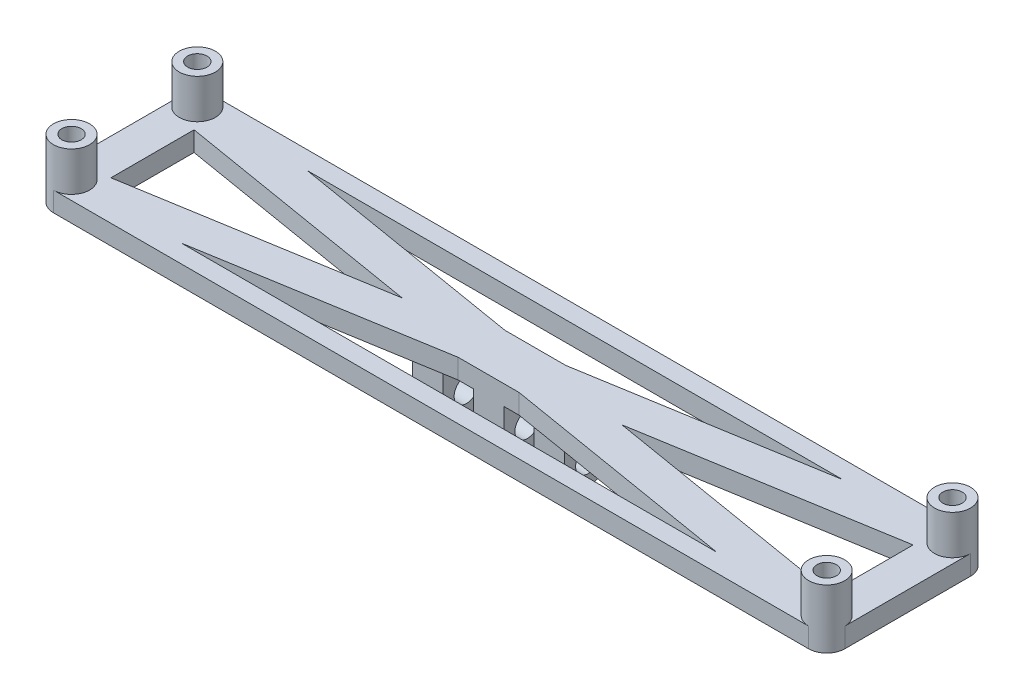
SolidWorks part; units mm, degrees
ref_plane "Front Plane" through (0, 0, 0) normal (0, 0, 1) x (1, 0, 0)
ref_plane "Top Plane" through (0, 0, 0) normal (0, 1, 0) x (1, 0, 0)
ref_plane "Right Plane" through (0, 0, 0) normal (1, 0, 0) x (0, 0, -1)
sketch "Sketch1" plane through (0, 0, 0) normal (0, 1, 0) x (1, 0, 0)
  line L1 (-38.36, 6.39) -> (-27.1925, 6.39) construction
  line L2 (-38.36, 6.39) -> (-38.36, -6.39) construction
  line L3 (-38.36, -6.39) -> (-36.525, -6.39) construction
  line L4 (38.36, 4.555) -> (38.36, 4.5297) construction
  line L7 (-38.0585, 8.2001) -> (-3.0899, 2.375) construction
  line L8 (-38.6615, 4.5799) -> (-11.1675, 0) construction
  line L10 (-38.6615, -4.5799) -> (-11.1675, 0) construction
  line L12 (11.1675, 0) -> (36.525, -4.224) construction
  line L13 (-3.0899, 2.375) -> (3.0899, 2.375) construction
  line L15 (-3.0899, -2.375) -> (3.0899, -2.375) construction
  line L17 (-38.36, 6.39) -> (-38.36, -6.39) construction
  line L18 (3.0899, 2.375) -> (16.1767, 4.555) construction
  line L19 (11.1675, 0) -> (36.525, 4.224) construction
  line L24 (3.0899, -2.375) -> (16.1767, -4.555) construction
  line L25 (-36.525, 6.39) -> (-36.525, -4.555) construction
  line L26 (-40.195, 6.39) -> (-40.195, -6.39) construction
  line L30 (-38.36, -6.39) -> (-36.525, -6.39) construction
  line L31 (-38.36, -4.555) -> (-36.525, -4.555) construction
  line L32 (-38.36, -8.225) -> (38.36, -8.225) construction
  line L33 (38.36, 4.555) -> (38.36, 4.5297) construction
  line L34 (40.195, 6.39) -> (40.195, -6.39) construction
  line L35 (36.525, 4.224) -> (36.525, -4.555) construction
  line L37 (16.1767, 4.555) -> (-38.36, 4.555) construction
  line L38 (38.36, 8.225) -> (-38.36, 8.225) construction
  line L39 (38.36, -4.5297) -> (38.6615, -4.5799) construction
  line L41 (-27.1925, 6.39) -> (-38.36, 6.39) construction
  line L42 (38.36, -4.5297) -> (38.36, -6.39) construction
  line L43 (38.36, -4.5297) -> (38.36, -6.39) construction
  line L44 (-16.1767, -4.555) -> (-3.0899, -2.375) construction
  line L45 (-16.1767, -4.555) -> (16.1767, -4.555) construction
  arc A0 (-38.0585, 8.2001) -> (-38.6615, 4.5799) centre (-38.36, 6.39) ccw construction
  arc A1 (38.0585, -8.2001) -> (38.6615, -4.5799) centre (38.36, -6.39) ccw construction
  arc A2 (-38.6615, -4.5799) -> (-38.0585, -8.2001) centre (-38.36, -6.39) ccw construction
  arc A3 (40.195, 6.39) -> (38.0585, 8.2001) centre (38.36, 6.39) ccw construction
  arc A4 (-36.525, 6.39) -> (-40.195, 6.39) centre (-38.36, 6.39) ccw construction
  arc A5 (-40.195, -6.39) -> (-36.525, -6.39) centre (-38.36, -6.39) ccw construction
  arc A8 (-38.36, -4.555) -> (-38.36, -8.225) centre (-38.36, -6.39) ccw construction
  arc A9 (38.36, -8.225) -> (38.36, -4.555) centre (38.36, -6.39) ccw construction
  arc A10 (40.195, 6.39) -> (38.0585, 8.2001) centre (38.36, 6.39) ccw construction
  arc A11 (38.0585, -8.2001) -> (40.195, -6.39) centre (38.36, -6.39) ccw construction
  arc A13 (-38.36, 8.225) -> (-38.36, 4.555) centre (-38.36, 6.39) ccw construction
  arc A14 (40.195, 6.39) -> (38.36, 8.225) centre (38.36, 6.39) ccw construction
  point P0 (0, 0)
  point P6 (0, 0)
  point P11 (0, 0)
  point P16 (0, 0)
  point P17 (-38.36, 0)
  point P26 (0, 6.39)
  point P35 (0, -6.39)
  point P43 (38.36, 0)
  dimension "D1" = 76.72
  dimension "D2" = 12.78
sketch "Sketch2" plane through (0, 0, 0) normal (0, 1, 0) x (1, 0, 0)
  line L0 (-38.36, 6.39) -> (38.36, -6.39) construction
  line L1 (38.36, -6.39) -> (-38.36, -6.39) construction
  line L2 (38.36, -6.39) -> (38.36, 6.39) construction
  line L3 (38.36, 6.39) -> (-38.36, 6.39) construction
  line L4 (-38.36, -6.39) -> (-38.36, 6.39) construction
  line L5 (38.36, -6.39) -> (-38.36, 6.39) construction
  line L6 (38.36, 6.39) -> (-38.36, -6.39) construction
  line L7 (-38.0585, 8.2001) -> (38.6615, -4.5799) construction
  line L8 (-38.6615, 4.5799) -> (38.0585, -8.2001) construction
  line L9 (-38.36, -6.39) -> (38.36, 6.39) construction
  line L10 (-38.6615, -4.5799) -> (38.0585, 8.2001) construction
  line L11 (-38.0585, -8.2001) -> (38.6615, 4.5799) construction
  line L12 (-38.36, 6.39) -> (-38.36, -6.39) construction
  line L19 (-36.525, 6.39) -> (-36.525, -6.39) construction
  line L20 (-40.195, 6.39) -> (-40.195, -6.39) construction
  line L21 (38.36, 6.39) -> (38.36, -6.39) construction
  line L22 (40.195, 6.39) -> (40.195, -6.39) construction
  line L23 (36.525, 6.39) -> (36.525, -6.39) construction
  line L24 (-38.36, 6.39) -> (38.36, 6.39) construction
  line L25 (-38.36, 8.225) -> (38.36, 8.225) construction
  line L26 (-38.36, 4.555) -> (38.36, 4.555) construction
  line L27 (-38.36, -6.39) -> (38.36, -6.39) construction
  line L28 (-38.36, -4.555) -> (38.36, -4.555) construction
  line L29 (-38.36, -8.225) -> (38.36, -8.225) construction
  line L31 (-7.715, 2.375) -> (7.715, 2.375)
  line L32 (-7.715, 2.375) -> (-7.715, -2.375)
  line L33 (-7.715, -2.375) -> (7.715, -2.375)
  line L34 (7.715, 2.375) -> (7.715, -2.375)
  line L35 (-7.715, 2.375) -> (7.715, -2.375) construction
  line L36 (-7.715, -2.375) -> (7.715, 2.375) construction
  arc A0 (-38.0585, 8.2001) -> (-38.6615, 4.5799) centre (-38.36, 6.39) ccw construction
  arc A1 (38.0585, -8.2001) -> (38.6615, -4.5799) centre (38.36, -6.39) ccw construction
  arc A2 (-38.6615, -4.5799) -> (-38.0585, -8.2001) centre (-38.36, -6.39) ccw construction
  arc A3 (38.6615, 4.5799) -> (38.0585, 8.2001) centre (38.36, 6.39) ccw construction
  arc A4 (-36.525, 6.39) -> (-40.195, 6.39) centre (-38.36, 6.39) ccw construction
  arc A5 (-40.195, -6.39) -> (-36.525, -6.39) centre (-38.36, -6.39) ccw construction
  arc A6 (40.195, 6.39) -> (36.525, 6.39) centre (38.36, 6.39) ccw construction
  arc A7 (36.525, -6.39) -> (40.195, -6.39) centre (38.36, -6.39) ccw construction
  arc A8 (-38.36, 8.225) -> (-38.36, 4.555) centre (-38.36, 6.39) ccw construction
  arc A9 (38.36, 4.555) -> (38.36, 8.225) centre (38.36, 6.39) ccw construction
  arc A10 (-38.36, -4.555) -> (-38.36, -8.225) centre (-38.36, -6.39) ccw construction
  arc A11 (38.36, -8.225) -> (38.36, -4.555) centre (38.36, -6.39) ccw construction
  point P0 (0, 0)
  point P7 (0, 0)
  point P12 (0, 0)
  point P17 (0, 0)
  point P18 (0, 0)
  point P25 (-38.36, 0)
  point P30 (38.36, 0)
  point P39 (0, 6.39)
  point P46 (0, -6.39)
  dimension "D1" = 15.43
  dimension "D2" = 4.75
sketch "Sketch3" plane through (0, 0, 0) normal (0, 1, 0) x (1, 0, 0)
  line L0 (-3.0899, 2.375) -> (3.0899, 2.375)
  line L2 (3.0899, -2.375) -> (27.1925, -6.39)
  line L3 (-3.0899, -2.375) -> (3.0899, -2.375)
  line L5 (-27.1925, 6.39) -> (-3.0899, 2.375)
  line L6 (-38.0585, 8.2001) -> (-3.0899, 2.375) construction
  line L7 (-36.525, 4.224) -> (-36.525, -4.224)
  line L8 (-36.525, 6.39) -> (-36.525, -4.555) construction
  line L9 (-38.6615, 4.5799) -> (-11.1675, 0) construction
  line L10 (-38.6615, -4.5799) -> (-11.1675, 0) construction
  line L11 (-36.525, -4.224) -> (-11.1675, 0)
  line L12 (-11.1675, 0) -> (-36.525, 4.224)
  line L13 (3.0899, 2.375) -> (27.1925, 6.39)
  line L14 (38.36, 6.39) -> (-38.36, 6.39) construction
  line L15 (-38.6615, -4.5799) -> (38.0585, 8.2001) construction
  line L16 (27.1925, 6.39) -> (-27.1925, 6.39)
  line L17 (0, 0) -> (32.5589, 0) construction
  line L19 (0, 0) -> (0, -14.525) construction
  line L20 (-27.1925, -6.39) -> (-3.0899, -2.375)
  line L21 (27.1925, -6.39) -> (-27.1925, -6.39)
  line L22 (36.525, -4.224) -> (11.1675, 0)
  line L23 (36.525, 4.224) -> (36.525, -4.224)
  line L24 (11.1675, 0) -> (36.525, 4.224)
  line L26 (38.36, -8.225) -> (-38.36, -8.225)
  line L27 (40.195, -6.39) -> (40.195, 6.39)
  line L28 (38.36, 8.225) -> (-38.36, 8.225)
  line L29 (-40.195, -6.39) -> (-40.195, 6.39)
  line L30 (40.195, -8.225) -> (-40.195, 8.225) construction
  line L31 (40.195, 8.225) -> (-40.195, -8.225) construction
  arc A0 (-40.195, 6.39) -> (-38.36, 8.225) centre (-38.36, 6.39) cw
  arc A1 (38.36, -8.225) -> (40.195, -6.39) centre (38.36, -6.39) ccw
  arc A2 (40.195, 6.39) -> (38.36, 8.225) centre (38.36, 6.39) ccw
  arc A3 (-38.36, -8.225) -> (-40.195, -6.39) centre (-38.36, -6.39) cw
  dimension "D3" = 1.835
  dimension "D4" = 1.835
  dimension "D1" = 16.45
  dimension "D2" = 80.39
extrude "Boss-Extrude2" add sketch "Sketch3" along normal blind 2
sketch "Sketch4" plane through (0, 2, 0) normal (0, 1, 0) x (1, 0, 0)
  circle A0 centre (-38.36, 6.39) radius 1.835
  circle A1 centre (-38.36, -6.39) radius 1.835
  circle A2 centre (38.36, 6.39) radius 1.835
  circle A3 centre (38.36, -6.39) radius 1.835
extrude "Boss-Extrude3" add sketch "Sketch4" along normal blind 4
ref_plane "Plane1" through (0, 6, 0) normal (0, 1, 0) x (1, 0, 0)
sketch "Sketch6" plane through (0, 6, 0) normal (0, 1, 0) x (1, 0, 0)
  circle A0 centre (-38.36, 6.39) radius 0.985
  circle A1 centre (-38.36, -6.39) radius 0.985
  circle A2 centre (38.36, 6.39) radius 0.985
  circle A3 centre (38.36, -6.39) radius 0.985
  dimension "D1" = 1.97
extrude "Cut-Extrude1" cut sketch "Sketch6" against normal blind 4
ref_plane "Plane2" through (7.715, 0, 0) normal (-1, 0, 0) x (0, 0, 1)
sketch "Sketch7" plane through (7.715, 0, 0) normal (-1, 0, 0) x (0, 0, 1)
  line L0 (-2.375, 0) -> (2.375, 0) construction
  line L1 (2.375, -2.775) -> (2.375, 0)
  line L2 (-2.375, -2.775) -> (-2.375, 0)
  line L4 (-2.375, 0) -> (2.375, 0)
  arc A0 (-2.375, -2.775) -> (2.375, -2.775) centre (0, -2.775) ccw
  circle A1 centre (0, -2.775) radius 1.25
  point P2 (0, 0)
  point P3 (0, 0)
  point P6 (2.3411, 0)
  point P10 (0, 0)
  point P11 (0, 0)
  point P12 (0, 0)
  point P13 (0, 0)
  dimension "D1" = 4.75
  dimension "D3" = 2.5
extrude "Boss-Extrude4" add sketch "Sketch7" along normal blind 3.086
ref_plane "Plane3" through (0, 0, 0) normal (-1, 0, 0) x (0, 0, 1)
sketch "Sketch8" plane through (0, 0, 0) normal (-1, 0, 0) x (0, 0, 1)
  line L3 (2.375, 0) -> (-2.375, 0)
  line L4 (-2.375, 0) -> (-2.375, -2.775)
  line L5 (2.375, -2.775) -> (2.375, 0)
  line L6 (2.375, 0) -> (-2.375, 0)
  line L7 (-2.375, 0) -> (-2.375, -2.775)
  line L8 (2.375, -2.775) -> (2.375, 0)
  circle A0 centre (0, -2.775) radius 1.25 construction
  arc A1 (-2.375, -2.775) -> (2.375, -2.775) centre (0, -2.775) ccw
  arc A2 (-2.375, -2.775) -> (2.375, -2.775) centre (0, -2.775) ccw
  circle A3 centre (0, -2.775) radius 1.25
  dimension "D1" = 0
extrude "Boss-Extrude5" add sketch "Sketch8" along normal mid plane 3.086
ref_plane "Plane4" through (-7.715, 0, 0) normal (1, 0, 0) x (0, 0, 1)
sketch "Sketch9" plane through (-7.715, 0, 0) normal (1, 0, 0) x (0, 0, 1)
  line L3 (-2.375, 0) -> (2.375, 0)
  line L4 (2.375, 0) -> (2.375, 2.775)
  line L5 (-2.375, 2.775) -> (-2.375, 0)
  line L6 (-2.375, 0) -> (2.375, 0)
  line L7 (2.375, 0) -> (2.375, 2.775)
  line L8 (-2.375, 2.775) -> (-2.375, 0)
  circle A0 centre (0, 2.775) radius 1.25 construction
  arc A1 (2.375, 2.775) -> (-2.375, 2.775) centre (0, 2.775) ccw
  arc A2 (2.375, 2.775) -> (-2.375, 2.775) centre (0, 2.775) ccw
  circle A3 centre (0, 2.775) radius 1.25
  dimension "D1" = 0
extrude "Boss-Extrude6" add sketch "Sketch9" along normal blind 3.086
